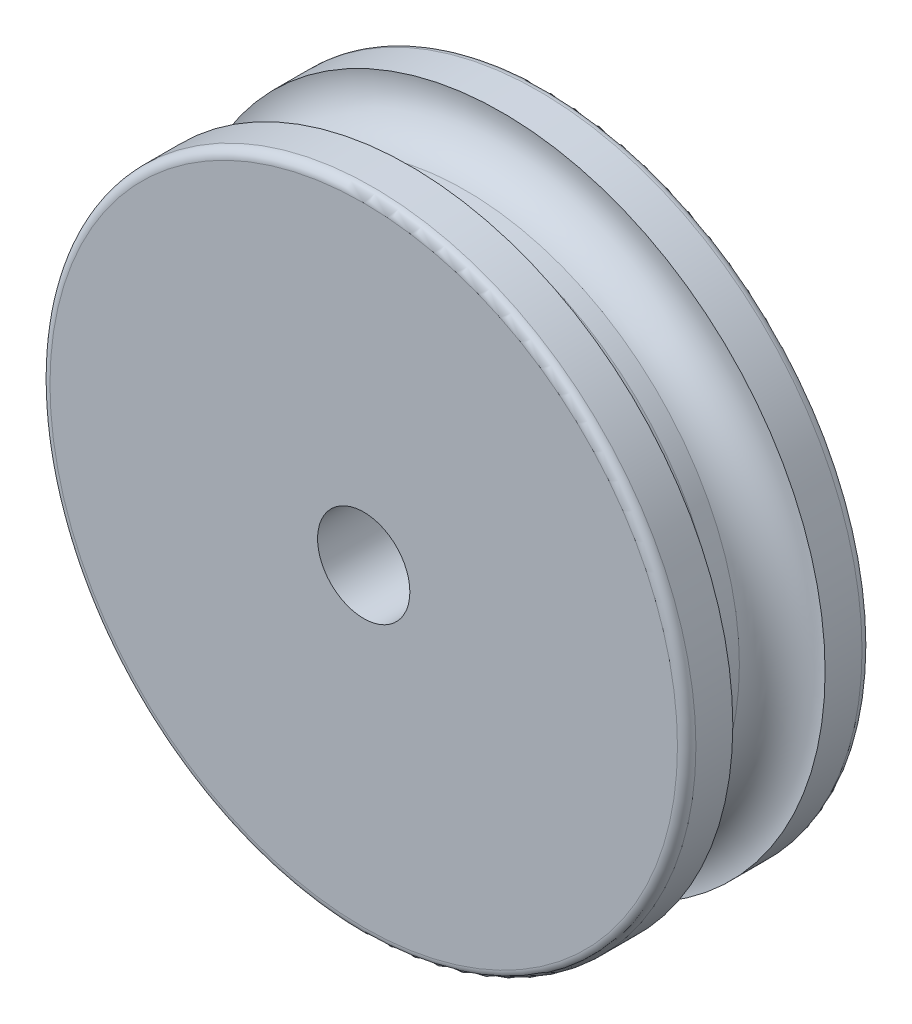
SolidWorks part; units mm, degrees
ref_plane "前视基准面" through (0, 0, 0) normal (0, 0, 1) x (1, 0, 0)
ref_plane "上视基准面" through (0, 0, 0) normal (0, 1, 0) x (1, 0, 0)
ref_plane "右视基准面" through (0, 0, 0) normal (1, 0, 0) x (0, 0, -1)
other "Configuration Table"
sketch "草图1" plane through (0, 0, 70.26) normal (0, 0, 1) x (1, 0, 0)
  circle A0 centre (-553.2347, 615.6264) radius 14.4381
  circle A1 centre (-553.2347, 615.6264) radius 70
extrude "凸台-拉伸1" add sketch "草图1" against normal up to surface (40 mm away)
sketch "草图2" plane through (0, 0, 70.26) normal (0, 0, 1) x (1, 0, 0)
  circle A0 centre (-553.2347, 615.6264) radius 10
  circle A1 centre (-553.2347, 615.6264) radius 14.4381
extrude "凸台-拉伸2" add sketch "草图2" against normal up to surface (40 mm away)
sketch "草图3" plane through (0, 0, 70.26) normal (0, 0, 1) x (1, 0, 0)
  point P0 (-553.2347, 615.6264)
ref_plane "基准面1" through (0, 615.6264, 0) normal (0, 1, 0) x (1, 0, 0)
sketch "草图4" plane through (0, 615.6264, 0) normal (0, 1, 0) x (1, 0, 0)
  line L0 (-493.8141, -48.26) -> (-493.8141, -52.26)
  line L1 (-483.2347, -40.26) -> (-483.2347, -60.26)
  line L2 (-553.2347, -70.26) -> (-553.2347, -6.3445) construction
  line L3 (-623.2347, -70.26) -> (-483.2347, -70.26) construction
  arc A0 (-483.2347, -40.26) -> (-493.8141, -48.26) centre (-484.5244, -49.5497) ccw
  arc A1 (-483.2347, -60.26) -> (-493.8141, -52.26) centre (-484.5244, -50.9703) cw
revolve "切除-旋转1" cut sketch "草图4" angle 360 about L2
fillet "圆角1" radius 2 2 edges at (-483.2347, 615.6264, 30.26) (-483.2347, 615.6264, 70.26)
